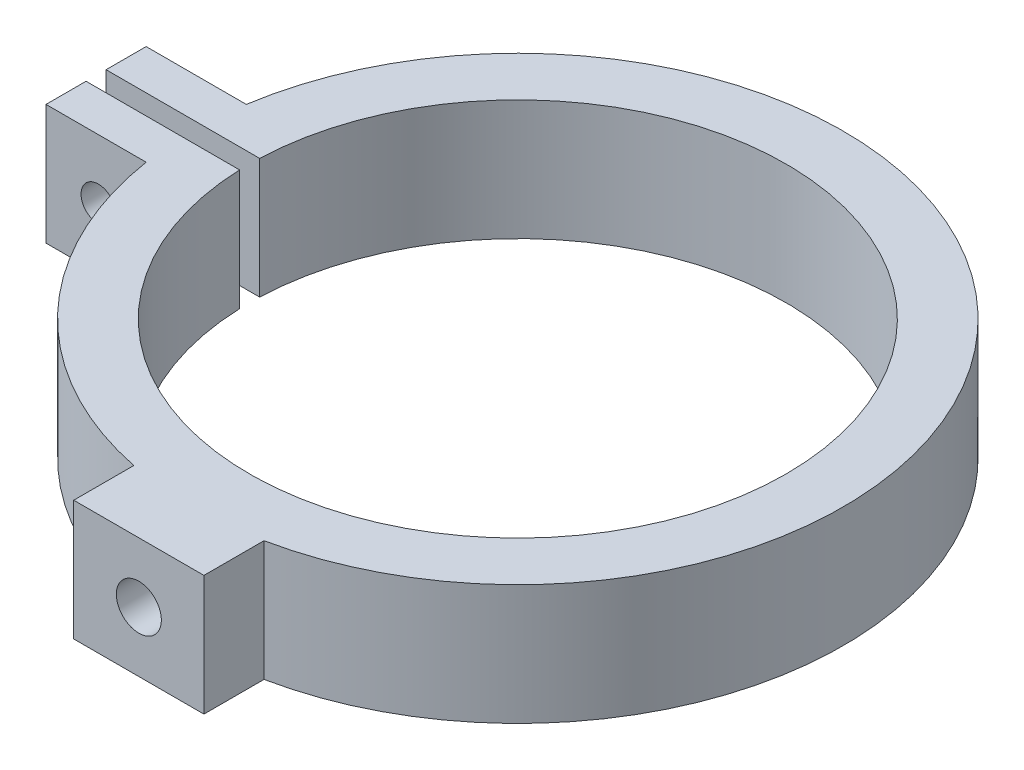
SolidWorks part; units mm, degrees
ref_plane "Front Plane" through (0, 0, 0) normal (0, 0, 1) x (1, 0, 0)
ref_plane "Top Plane" through (0, 0, 0) normal (0, 1, 0) x (1, 0, 0)
ref_plane "Right Plane" through (0, 0, 0) normal (1, 0, 0) x (0, 0, -1)
sketch "Sketch1" plane through (0, 0, 0) normal (0, 1, 0) x (1, 0, 0)
  line L0 (6.5, -31.8434) -> (6.5, -37.8434)
  line L1 (6.5, -37.8434) -> (-6.5, -37.8434)
  line L2 (-6.5, -37.8434) -> (-6.5, -31.8434)
  line L3 (0, -37.8434) -> (0, 0) construction
  circle A0 centre (0, 0) radius 26.8
  arc A1 (6.5, -31.8434) -> (-6.5, -31.8434) centre (0, 0) ccw
  point P9 (11.1377, -38.4386)
  dimension "D1" = 53.6
  dimension "D2" = 65
  dimension "D3" = 13
  dimension "D4" = 6
extrude "Boss-Extrude1" add sketch "Sketch1" along normal mid plane 12
hole_wizard "CBORE for #8 Socket Head Cap Screw1" positions "3DSketch1" profile "Sketch2" counterbore size "#8" standard "ANSI Inch"
sketch3d "3DSketch1"
  point P0 (0, 0, 26.8)
  point P4 (0, 0, 0)
sketch "Sketch2" plane through (0, 0, 26.8) normal (1, 0, 0) x (0, 1, 0)
  line L0 (0, 0) -> (0, 11.0434)
  line L1 (0, 11.0434) -> (2.2479, 11.0434)
  line L3 (2.2479, 11.0434) -> (2.2479, 4.1656)
  line L4 (2.2479, 4.1656) -> (3.9688, 4.1656)
  line L5 (3.9688, 4.1656) -> (3.9688, 0)
  line L7 (3.9688, 0) -> (0, 0)
  line L11 (0, -6.35) -> (0, 107.95) construction
  dimension "Thru Hole Dia." = 4.4958
  dimension "Thru Hole Depth" = 11.0434
  dimension "C'Bore Dia." = 7.9375
  dimension "C'Bore Depth" = 4.1656
sketch "Sketch3" plane through (0, 6, 0) normal (0, 1, 0) x (1, 0, 0)
  line L1 (0, 1) -> (-37.2978, 1)
  line L2 (0, 1) -> (0, -1)
  line L3 (0, -1) -> (-37.2978, -1)
  line L4 (-37.2978, 1) -> (-37.2978, -1)
  dimension "D1" = 2
extrude "Cut-Extrude1" cut sketch "Sketch3" against normal blind 12
sketch "Sketch4" plane through (0, 6, 0) normal (0, 1, 0) x (1, 0, 0)
  line L0 (-32.4846, -1) -> (-42.1131, -1)
  line L1 (-42.1131, -1) -> (-42.1131, -5)
  line L2 (-42.1131, -5) -> (-32.1131, -5)
  line L3 (-32.4846, 1) -> (-42.1131, 1)
  line L4 (-42.1131, 1) -> (-42.1131, 5)
  line L5 (-42.1131, 5) -> (-32.1131, 5)
  arc A0 (-32.4846, -1) -> (-6.5, -31.8434) centre (0, 0) ccw construction
  arc A1 (6.5, -31.8434) -> (-32.4846, 1) centre (0, 0) ccw construction
  arc A2 (-32.1131, 5) -> (-32.4846, 1) centre (0, 0) ccw
  arc A3 (-32.4846, -1) -> (-32.1131, -5) centre (0, 0) ccw
  dimension "D1" = 4
  dimension "D2" = 10
extrude "Boss-Extrude2" add sketch "Sketch4" against normal blind 12
hole_wizard "#8-32 Tapped Hole1" positions "Sketch5" profile "Sketch7" tap size "#8-32" standard "ANSI Inch" end condition through all
sketch "Sketch5" plane through (0, 0, -5) normal (0, 0, -1) x (-1, 0, 0)
  point P0 (36.8856, 0)
sketch "Sketch7" plane through (-36.8856, 0, -5) normal (1, 0, 0) x (0, 1, 0)
  line L0 (0, 0) -> (0, 42.8434)
  line L1 (0, 42.8434) -> (1.7272, 42.8434)
  line L2 (1.7272, 42.8434) -> (1.7272, 0)
  line L5 (1.7272, 0) -> (0, 0)
  line L11 (0, -6.35) -> (0, 107.95) construction
  dimension "Thru Tap Drill Dia." = 3.4544
  dimension "Thru Tap Drill Depth" = 42.8434
cosmetic thread "Hole Thread1" parameters "D2"=4.1656
hole_wizard "#8 Clearance Hole1" positions "Sketch8" profile "Sketch10" hole size "#8" standard "ANSI Inch"
sketch "Sketch8" plane through (0, 0, -5) normal (0, 0, -1) x (-1, 0, 0)
  point P0 (36.8856, 0)
sketch "Sketch10" plane through (-36.8856, 0, -5) normal (1, 0, 0) x (0, 1, 0)
  line L0 (0, 0) -> (0, 5.4766)
  line L1 (0, 5.4766) -> (2.4574, 4)
  line L2 (2.4574, 4) -> (2.4574, 0)
  line L5 (2.4574, 0) -> (0, 0)
  line L10 (0, 5.4766) -> (-2.4574, 4) construction
  line L11 (0, -6.35) -> (0, 107.95) construction
  dimension "Hole Dia." = 4.9149
  dimension "Hole Depth" = 4
  dimension "Drill Angle" = 118
